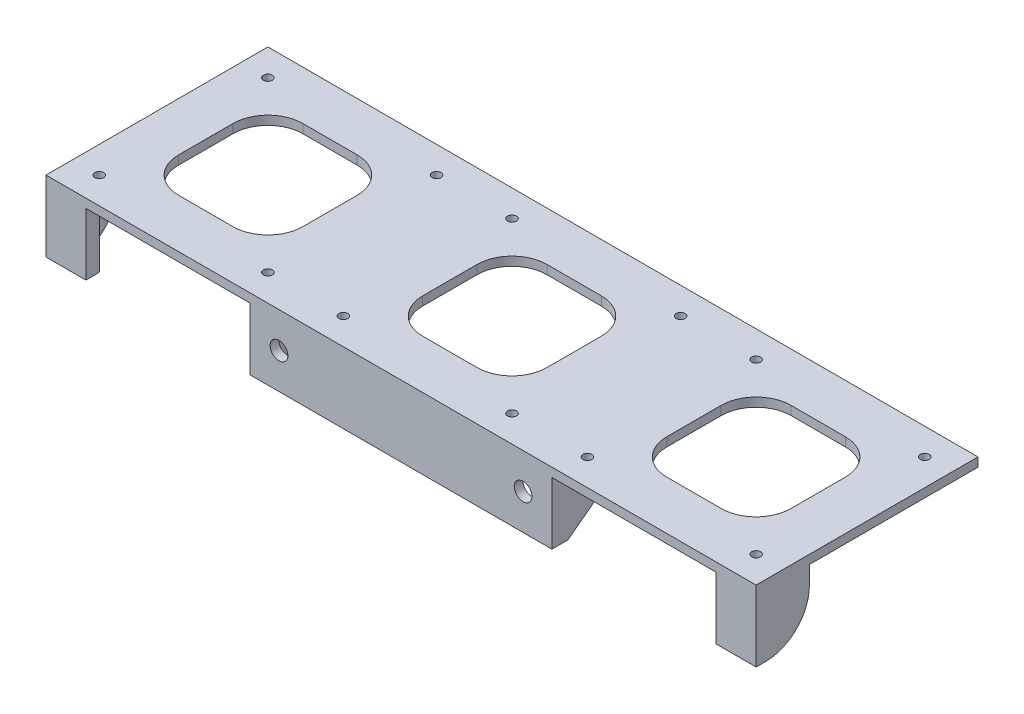
SolidWorks part; units mm, degrees
ref_plane "Front Plane" through (0, 0, 0) normal (0, 0, 1) x (1, 0, 0)
ref_plane "Top Plane" through (0, 0, 0) normal (0, 1, 0) x (1, 0, 0)
ref_plane "Right Plane" through (0, 0, 0) normal (1, 0, 0) x (0, 0, -1)
sketch "Sketch1" plane through (0, 0, 0) normal (0, 1, 0) x (1, 0, 0)
  line L5 (0, 0) -> (203.2, 0)
  line L6 (0, 0) -> (0, 63.5)
  line L7 (0, 63.5) -> (203.2, 63.5)
  line L8 (203.2, 0) -> (203.2, 63.5)
  circle A0 centre (7.62, 55.88) radius 1.27
  circle A1 centre (55.88, 55.88) radius 1.27
  circle A2 centre (7.62, 7.62) radius 1.27
  circle A3 centre (55.88, 7.62) radius 1.27
  circle A4 centre (77.47, 55.88) radius 1.27
  circle A5 centre (125.73, 55.88) radius 1.27
  circle A6 centre (125.73, 7.62) radius 1.27
  circle A7 centre (77.47, 7.62) radius 1.27
  circle A8 centre (147.32, 55.88) radius 1.27
  circle A9 centre (195.58, 55.88) radius 1.27
  circle A10 centre (195.58, 7.62) radius 1.27
  circle A11 centre (147.32, 7.62) radius 1.27
  point P13 (88.133, 55.88)
  dimension "D3" = 2.54
  dimension "D1" = 48.26
  dimension "D2" = 48.26
  dimension "D4" = 7.62
  dimension "D5" = 7.62
  dimension "D6" = 7.62
  dimension "D8" = 21.59
  dimension "D9" = 7.62
  dimension "D7" = 3
extrude "Boss-Extrude1" add sketch "Sketch1" along normal blind 2.54
sketch "Sketch2" plane through (0, 0, 0) normal (0, 0, 1) x (1, 0, 0)
  line L0 (66.675, -7.62) -> (136.525, -7.62) construction
  line L1 (0, 0) -> (203.2, 0) construction
  line L2 (0, 2.54) -> (203.2, 2.54) construction
  line L3 (58.42, 2.54) -> (144.78, 2.54)
  line L4 (58.42, 2.54) -> (58.42, -17.78)
  line L5 (58.42, -17.78) -> (144.78, -17.78)
  line L6 (144.78, 2.54) -> (144.78, -17.78)
  circle A0 centre (66.675, -7.62) radius 2.54
  circle A1 centre (136.525, -7.62) radius 2.54
  point P4 (101.6, 0)
  point P5 (101.6, -7.62)
  point P14 (101.6, -17.78)
  point P15 (0, 0)
  point P16 (0, 0)
  dimension "D2" = 5.08
  dimension "D1" = 69.85
  dimension "D3" = 7.62
  dimension "D4" = 20.32
  dimension "D5" = 86.36
extrude "Boss-Extrude2" add sketch "Sketch2" against normal blind 2.54 contours L4 L5 L6 L3
sketch "Sketch3" plane through (0, 0, 0) normal (0, -1, 0) x (1, 0, 0)
  line L1 (58.42, -2.54) -> (62.23, -2.54)
  line L2 (58.42, -2.54) -> (58.42, -27.94)
  line L3 (58.42, -27.94) -> (62.23, -27.94)
  line L4 (62.23, -2.54) -> (62.23, -27.94)
  line L5 (144.78, -2.54) -> (140.97, -2.54)
  line L6 (144.78, -2.54) -> (144.78, -27.94)
  line L7 (144.78, -27.94) -> (140.97, -27.94)
  line L8 (140.97, -2.54) -> (140.97, -27.94)
  dimension "D1" = 25.4
  dimension "D2" = 3.81
extrude "Boss-Extrude3" add sketch "Sketch3" along normal up to surface (17.78 mm away) up to face at (101.6, -17.78, -1.27)
chamfer "Chamfer1" distance 17.62 angle 53 2 edges at (142.875, -17.78, -27.94) (60.325, -17.78, -27.94)
sketch "Sketch4" plane through (0, 0, 0) normal (0, -1, 0) x (1, 0, 0)
  line L0 (0, -63.5) -> (0, 0) construction
  line L1 (13.97, -13.97) -> (49.53, -13.97)
  line L2 (13.97, -13.97) -> (13.97, -49.53)
  line L3 (13.97, -49.53) -> (49.53, -49.53)
  line L4 (49.53, -13.97) -> (49.53, -49.53)
  line L5 (83.82, -13.97) -> (119.38, -13.97)
  line L6 (83.82, -13.97) -> (83.82, -49.53)
  line L7 (83.82, -49.53) -> (119.38, -49.53)
  line L8 (119.38, -13.97) -> (119.38, -49.53)
  line L9 (153.67, -13.97) -> (189.23, -13.97)
  line L10 (153.67, -13.97) -> (153.67, -49.53)
  line L11 (153.67, -49.53) -> (189.23, -49.53)
  line L12 (189.23, -13.97) -> (189.23, -49.53)
  line L13 (7.62, -7.62) -> (55.88, -7.62) construction
  line L14 (77.47, -7.62) -> (125.73, -7.62) construction
  line L15 (147.32, -7.62) -> (195.58, -7.62) construction
  point P12 (0, -31.75)
  point P13 (13.97, -31.75)
  point P28 (171.45, -7.62)
  point P29 (101.6, -7.62)
  point P30 (31.75, -7.62)
  point P31 (31.75, -13.97)
  point P32 (101.6, -13.97)
  point P33 (171.45, -13.97)
  point P34 (0, 0)
  point P35 (0, 0)
  point P36 (0, 0)
  dimension "D1" = 35.56
extrude "Cut-Extrude1" cut sketch "Sketch4" against normal through all
fillet "Fillet1" radius 10 12 edges at (13.97, 1.27, -49.53) (83.82, 1.27, -49.53) (153.67, 1.27, -49.53) (49.53, 1.27, -49.53) (119.38, 1.27, -49.53) (189.23, 1.27, -49.53) (189.23, 1.27, -13.97) (119.38, 1.27, -13.97) (49.53, 1.27, -13.97) (153.67, 1.27, -13.97) (83.82, 1.27, -13.97) (13.97, 1.27, -13.97)
sketch "Sketch5" plane through (0, 0, 0) normal (0, -1, 0) x (1, 0, 0)
  line L1 (0, 0) -> (5.08, 0)
  line L2 (0, 0) -> (0, -15.24)
  line L3 (0, -15.24) -> (5.08, -15.24)
  line L4 (5.08, -3.81) -> (5.08, -15.24)
  line L5 (203.2, 0) -> (191.77, 0)
  line L6 (203.2, 0) -> (203.2, -15.24)
  line L7 (203.2, -15.24) -> (198.12, -15.24)
  line L8 (198.12, -3.81) -> (198.12, -15.24)
  line L9 (5.08, 0) -> (11.43, 0)
  line L11 (5.08, -3.81) -> (11.43, -3.81)
  line L12 (11.43, 0) -> (11.43, -3.81)
  line L15 (198.12, -3.81) -> (191.77, -3.81)
  line L16 (191.77, 0) -> (191.77, -3.81)
  point P16 (0, 0)
  point P17 (0, 0)
  point P18 (188.9384, 0)
  point P19 (0, 0)
  line M52 (58.42, 0) -> (0, 0)
  line M53 (0, 0) -> (0, -63.5)
  line M55 (203.2, -63.5) -> (203.2, 0)
  line M56 (203.2, 0) -> (144.78, 0)
  dimension "D1" = 15.24
  dimension "D2" = 5.08
  dimension "D3" = 3.81
  dimension "D4" = 6.35
  dimension "D5" = 5.08
extrude "Boss-Extrude4" add sketch "Sketch5" along normal up to surface (17.78 mm away) contours L8 L7 M56 M55 | L12 L3 L4 L11 M52 M53 up to face at (101.6, -17.78, -2.9137)
fillet "Fillet2" radius 12.54 2 edges at (200.66, -17.78, -15.24) (2.54, -17.78, -15.24)
